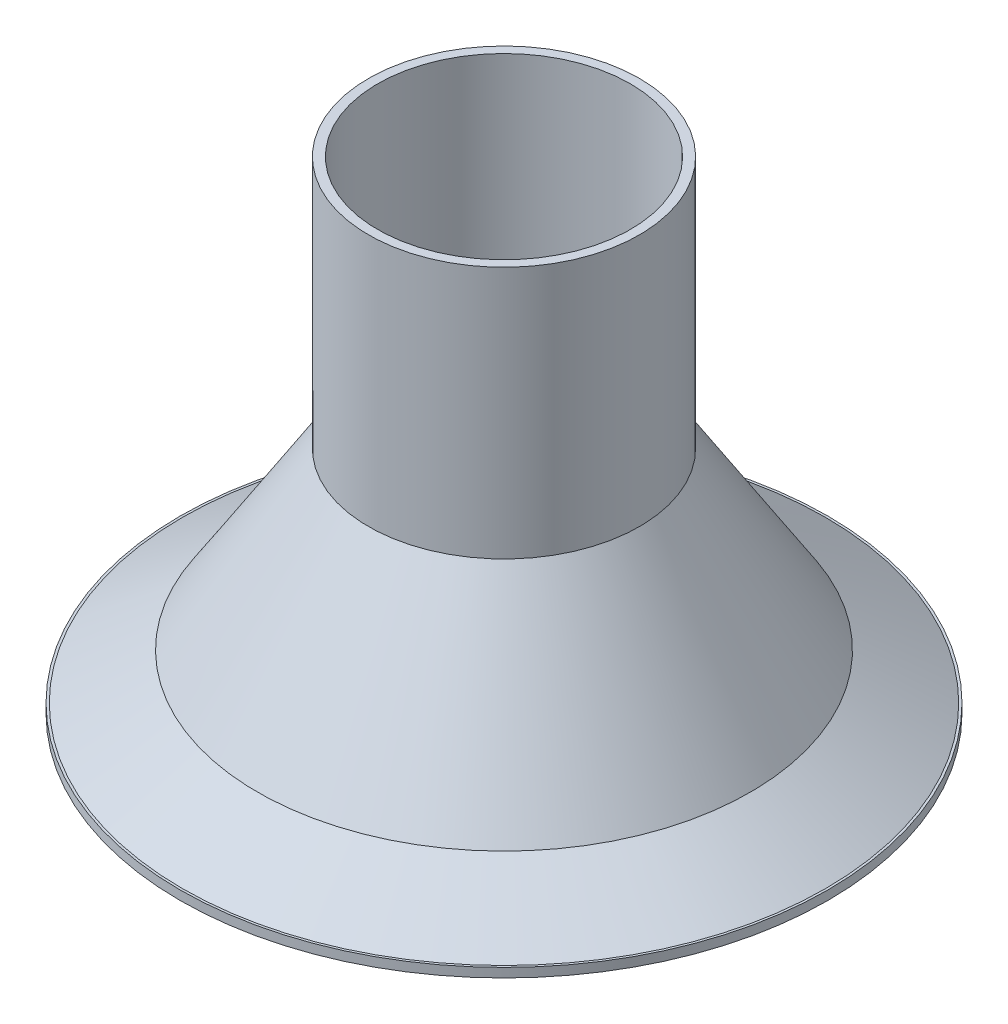
SolidWorks part; units mm, degrees
ref_plane "Front Plane" through (0, 0, 0) normal (0, 0, 1) x (1, 0, 0)
ref_plane "Top Plane" through (0, 0, 0) normal (0, 1, 0) x (1, 0, 0)
ref_plane "Right Plane" through (0, 0, 0) normal (1, 0, 0) x (0, 0, -1)
sketch "Sketch1" plane through (0, 0, 0) normal (0, 0, 1) x (1, 0, 0)
  line L0 (0, 0) -> (0, 42) construction
  line L1 (0, 0) -> (-29, 0) construction
  line L2 (-29, 0) -> (-29, 42) construction
  line L3 (-29, 42) -> (0, 42) construction
  line L4 (-29, 0) -> (-29, 0.8) construction
  line L6 (-11.8, 20) -> (-11.8, 42) construction
  line L7 (-11.8, 42) -> (-11, 42) construction
  line L11 (-29, 0) -> (-23.5605, 0) construction
  line L12 (-29, 0.8) -> (-24, 0.8) construction
  line L13 (-24, 0.8) -> (-11.8, 20) construction
  line L14 (-11, 19.7673) -> (-23.5605, 0) construction
  line L15 (0, 0) -> (0, -1) construction
  line L16 (0, -1) -> (-29, -1) construction
  line L17 (-11, 19.7673) -> (-11, 42) construction
  line L18 (-29, -1) -> (-29, 0) construction
  line L19 (-29, -2) -> (-23.5605, -2) construction
  line L20 (-11, -21.7673) -> (-23.5605, -2) construction
  line L21 (-11, -21.7673) -> (-11, -44) construction
  line L22 (-11.8, -44) -> (-11, -44) construction
  line L23 (-11.8, -22) -> (-11.8, -44) construction
  line L24 (-24, -2.8) -> (-11.8, -22) construction
  line L25 (-29, -2.8) -> (-24, -2.8) construction
  line L26 (-29, -2) -> (-29, -2.8) construction
  line L27 (-28, 0.8) -> (-28, 1.8) construction
  line L28 (-28, 1.8) -> (-21.4583, 4.8) construction
  line L29 (-21.4583, 4.8) -> (-24, 0.8) construction
  line L30 (-24, 0.8) -> (-28, 0.8) construction
  line L31 (-21.4583, -6.8) -> (-24, -2.8) construction
  line L32 (-28, -3.8) -> (-21.4583, -6.8) construction
  line L33 (-28, -2.8) -> (-28, -3.8) construction
  line L34 (-24, -2.8) -> (-28, -2.8) construction
  dimension "D10" = 0.8
  dimension "D11" = 1
  dimension "D14" = 57.567
  dimension "D2" = 29
  dimension "D3" = 0.8
  dimension "D4" = 42
  dimension "D5" = 22
  dimension "D6" = 11
  dimension "D7" = 1
  dimension "D8" = 1
  dimension "D9" = 5
  dimension "D12" = 4
sketch "Sketch2" plane through (0, 0, 0) normal (0, 0, 1) x (1, 0, 0)
  line L0 (-28, 1.8) -> (-21.4583, 4.8) construction
  line L1 (-28, 0.8) -> (-28, 1.8) construction
  line L2 (-29, 0.8) -> (-24, 0.8) construction
  line L3 (-11, 19.7673) -> (-23.5605, 0) construction
  line L4 (-24, 0.8) -> (-11.8, 20) construction
  line L5 (-11, 19.7673) -> (-11, 42) construction
  line L6 (-11.8, 20) -> (-11.8, 42) construction
  line L7 (-28, 1.8) -> (-21.4583, 4.8)
  line L8 (-28, 0.8) -> (-28, 1.8)
  line L9 (-29, 0.8) -> (-28, 0.8)
  line L10 (-11, 19.7673) -> (-23.5605, 0)
  line L11 (-21.4583, 4.8) -> (-11.8, 20)
  line L12 (-11, 19.7673) -> (-11, 42)
  line L13 (-11.8, 20) -> (-11.8, 42)
  line L14 (-29, 0.8) -> (-29, 0)
  line L15 (-29, 0) -> (-23.5605, 0)
  line L16 (-11.8, 42) -> (-11, 42)
revolve "Revolve2" add sketch "Sketch2" angle 360 about L0
sketch "Sketch3" plane through (0, 0, 0) normal (0, 0, 1) x (1, 0, 0)
  line L0 (-28, 0.8) -> (-28, 1.8)
  line L1 (-29, 0.8) -> (-28.2, 0.8)
  line L2 (-29, 0.8) -> (-29, 0)
  line L3 (-29, 0) -> (-28.2, 0)
  line L4 (-28.2, 0.8) -> (-28.2, 0)
  line L5 (28, 1.8) -> (28, 0.8)
  line L6 (28, 1.8) -> (28, 0.8) construction
  line L7 (-28, 0.8) -> (-28, 1.8) construction
  line L8 (-29, 0) -> (-29, 0.8)
  line L9 (29, 0.8) -> (29, 0)
  line L10 (29, 0.8) -> (29, 0) construction
  line L11 (-29, 0) -> (-29, 0.8) construction
  line L12 (0, 0) -> (0, 42) construction
  line L13 (11, 42) -> (-11, 42) construction
  dimension "D1" = 0.2
revolve "Cut-Revolve1" cut sketch "Sketch3" angle 360 about L12
sketch "Sketch4" plane through (0, 0, 0) normal (0, 0, 1) x (1, 0, 0)
  line L0 (-28, 0.8) -> (-28, 1.8)
  line L1 (28, 1.8) -> (28, 0.8)
  line L2 (28, 1.8) -> (28, 0.8) construction
  line L3 (-28, 0.8) -> (-28, 1.8)
  line L4 (-28, 1.8) -> (-21.4583, 4.8)
  line L5 (21.4583, 4.8) -> (28, 1.8)
  line L6 (21.4583, 4.8) -> (28, 1.8) construction
  line L7 (-28, 1.8) -> (-21.4583, 4.8)
  line L8 (-21.4583, 4.8) -> (-28, 0.8)
  line L10 (0, 0) -> (0, 55.3903) construction
revolve "Cut-Revolve2" cut sketch "Sketch4" angle 360 about L10
